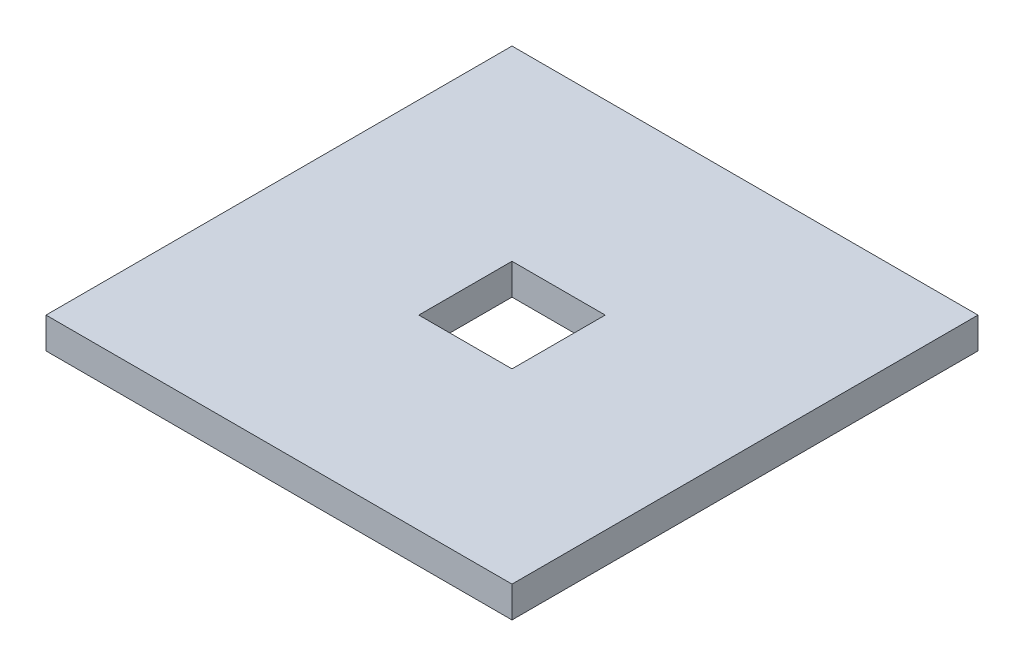
SolidWorks part; units mm, degrees
ref_plane "前视基准面" through (0, 0, 0) normal (0, 0, 1) x (1, 0, 0)
ref_plane "上视基准面" through (0, 0, 0) normal (0, 1, 0) x (1, 0, 0)
ref_plane "右视基准面" through (0, 0, 0) normal (1, 0, 0) x (0, 0, -1)
sketch "Sketch1" plane through (0, 0, 0) normal (0, 1, 0) x (1, 0, 0)
  line L1 (0, 0) -> (1500, 0)
  line L2 (0, 0) -> (0, 1500)
  line L3 (0, 1500) -> (1500, 1500)
  line L4 (1500, 0) -> (1500, 1500)
  line L5 (600, 900) -> (900, 900)
  line L6 (600, 900) -> (600, 600)
  line L7 (600, 600) -> (900, 600)
  line L8 (900, 900) -> (900, 600)
  dimension "D1" = 1500
  dimension "D2" = 1500
  dimension "D3" = 300
  dimension "D4" = 300
  dimension "D5" = 600
  dimension "D6" = 600
extrude "Boss-Extrude1" add sketch "Sketch1" along normal blind 100 contours L1 L4 L3 L2 L5 L8 L7 L6
